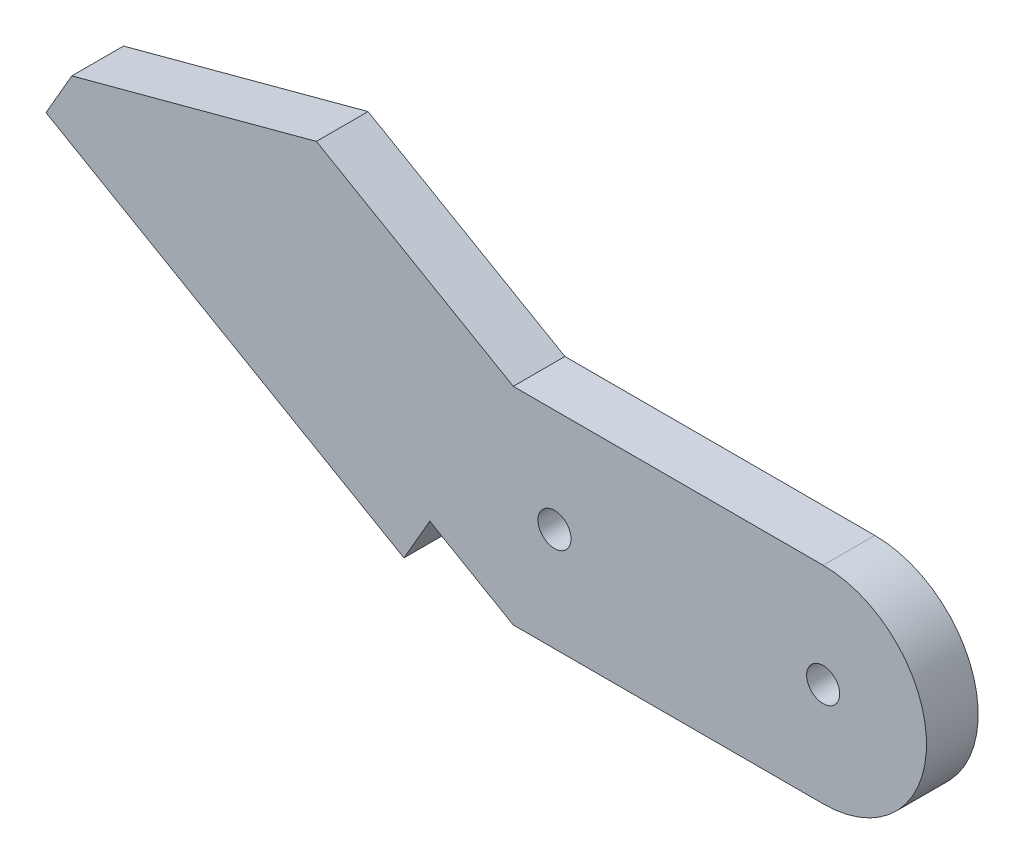
SolidWorks part; units mm, degrees
ref_plane "Front Plane" through (0, 0, 0) normal (1, 0, 0) x (0, 1, 0)
ref_plane "Top Plane" through (0, 0, 0) normal (0, 0, 1) x (0, 1, 0)
ref_plane "Right Plane" through (0, 0, 0) normal (0, 1, 0) x (-1, 0, 0)
sketch "Sketch2" plane through (0, 0, 0) normal (0, 0, 1) x (0, 1, 0)
  line L0 (-10, 0) -> (-10, 30)
  line L2 (10, 29.9928) -> (10, 0)
  line L7 (10, 29.9928) -> (21, 49.0453)
  line L8 (14.6589, 72.7105) -> (10.3288, 75.2105)
  line L9 (10.3288, 75.2105) -> (-9.6712, 40.5695)
  line L10 (-10, 30) -> (-5.3411, 38.0695)
  line L11 (-5.3411, 38.0695) -> (-9.6712, 40.5695)
  line L12 (-10, 24.1524) -> (-0.9928, 24.1524) construction
  line L13 (14.6589, 72.7105) -> (21, 49.0453)
  circle A0 centre (0, 0) radius 1.6
  circle A1 centre (0, 26) radius 1.6
  arc A3 (-10, 0) -> (10, 0) centre (0, 0) ccw
  dimension "D1" = 3.2
  dimension "D2" = 3.2
  dimension "D4" = 20
  dimension "D3" = 26
  dimension "D5" = 30
  dimension "D6" = 5
  dimension "D7" = 135
  dimension "D8" = 40
  dimension "D9" = 60
  dimension "D10" = 5
  dimension "D11" = 22
  dimension "D12" = 24.5
extrude "Boss-Extrude1" add sketch "Sketch2" along normal blind 5
